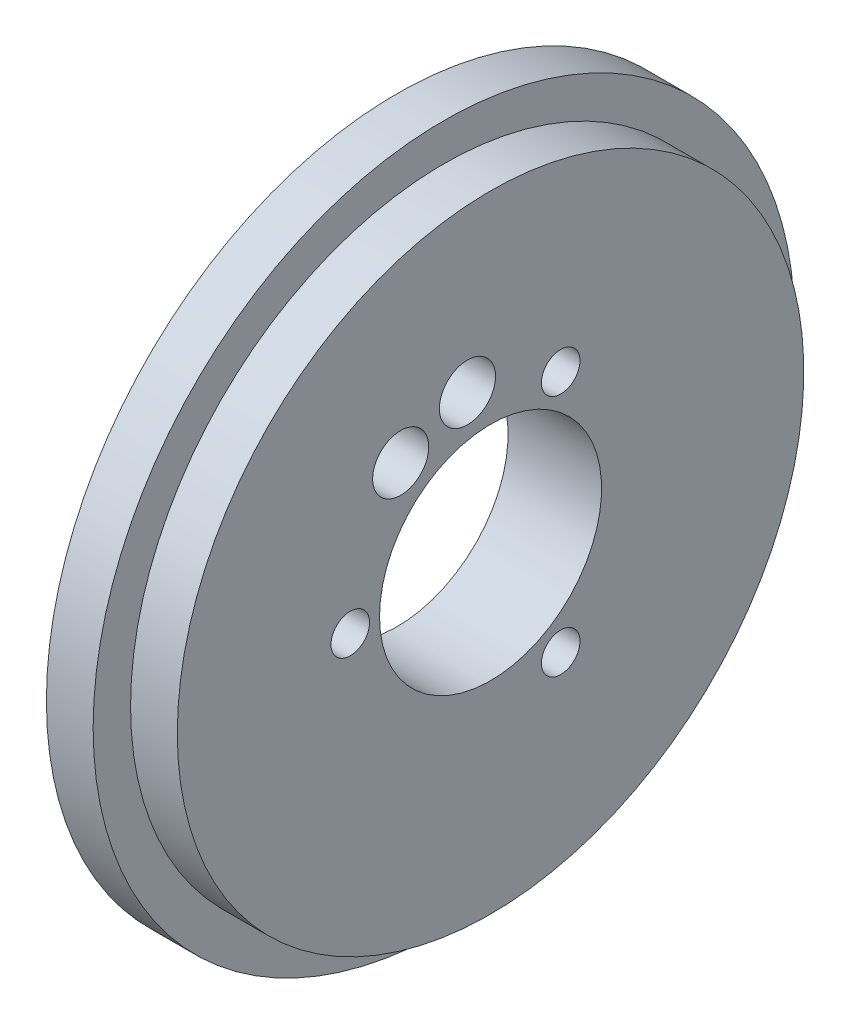
SolidWorks part; units mm, degrees
material "Alumina"
ref_plane "Front Plane" through (0, 0, 0) normal (0, 0, 1) x (1, 0, 0)
ref_plane "Top Plane" through (0, 0, 0) normal (0, 1, 0) x (1, 0, 0)
ref_plane "Right Plane" through (0, 0, 0) normal (1, 0, 0) x (0, 0, -1)
sketch "Axial profile (mm)" plane through (0, 0, 0) normal (0, 0, 1) x (1, 0, 0)
  line L0 (-110, 0) -> (75, 0) construction
  line L1 (135.7, 9.5) -> (143.7, 9.5)
  line L2 (143.7, 9.5) -> (143.7, 26.8)
  line L3 (143.7, 26.8) -> (139.7, 26.8)
  line L4 (139.7, 26.8) -> (139.7, 30)
  line L5 (139.7, 30) -> (135.7, 30)
  line L6 (135.7, 30) -> (135.7, 9.5)
revolve "Full revolution" add sketch "Axial profile (mm)" angle 360 about L0
sketch "Sketch2" plane through (0, 0, 0) normal (1, 0, 0) x (0, 0, -1)
  circle A0 centre (-1.9774, 12.8487) radius 2.4
  circle A1 centre (-7.6872, 10.4836) radius 2.4
  circle A2 centre (-12, 0) radius 1.65
  circle A3 centre (6, -10.3923) radius 1.65
  circle A4 centre (6, 10.3923) radius 1.65
extrude "Axial holes" cut sketch "Sketch2" along normal through all and the other way through all
